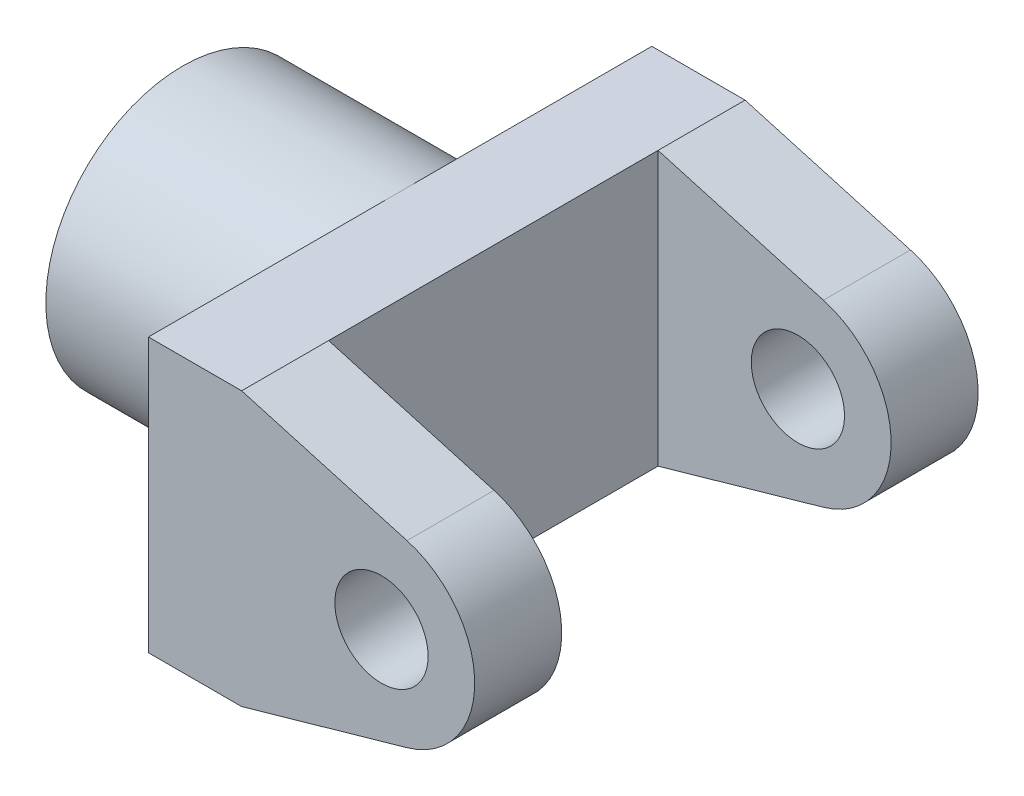
SolidWorks part; units mm, degrees
ref_plane "Front" through (0, 0, 0) normal (0, 0, 1) x (1, 0, 0)
ref_plane "Top" through (0, 0, 0) normal (0, 1, 0) x (1, 0, 0)
ref_plane "Right" through (0, 0, 0) normal (1, 0, 0) x (0, 0, -1)
sketch "Sketch2" plane through (0, 0, 0) normal (0, 0, 1) x (1, 0, 0)
  line L0 (-75, -44) -> (-75, 44)
  line L1 (0, 0) -> (-86.7621, 0) construction
  line L2 (-45, -44) -> (-45, 44)
  line L3 (-75, 44) -> (-45, 44)
  line L4 (-45, 44) -> (8.2128, 28.854)
  line L5 (-75, -44) -> (-45, -44)
  line L6 (-45, -44) -> (8.2128, -28.854)
  circle A0 centre (0, 0) radius 15
  arc A1 (4.5356, -29.6552) -> (4.5356, 29.6552) centre (0, 0) ccw
  circle A2 centre (0, 0) radius 30
  point P6 (-45, 0)
  point P7 (-75, 0)
  point P9 (-75, 0)
  point P15 (-45, 0)
  dimension "D1" = 30
  dimension "D2" = 60
  dimension "D7" = 60
  dimension "D3" = 30
  dimension "D4" = 75
  dimension "D5" = 88
  dimension "D6" = 88
extrude "Boss-Extrude1" add sketch "Sketch2" along normal blind 162
sketch "Sketch3" plane through (0, -44, 0) normal (0, -1, 0) x (1, 0, 0)
  line L0 (-45, 162) -> (-45, 0) construction
  line L1 (-45, 134) -> (30, 134)
  line L2 (-45, 134) -> (-45, 28)
  line L3 (-45, 28) -> (30, 28)
  line L4 (30, 134) -> (30, 28)
  line L5 (30, 0) -> (30, 162) construction
  line L6 (-75, 162) -> (-75, 0) construction
  point P10 (-75, 81)
  point P11 (-45, 81)
  dimension "D1" = 106
extrude "Cut-Extrude1" cut sketch "Sketch3" against normal through all
sketch "Sketch4" plane through (-75, 0, 0) normal (-1, 0, 0) x (0, 0, 1)
  line L0 (0, -44) -> (0, 44) construction
  circle A0 centre (81, 0) radius 44
  circle A1 centre (81, 0) radius 25
  point P3 (37.0051, -0.667)
  dimension "D1" = 88
  dimension "D2" = 50
  dimension "D3" = 81
extrude "Boss-Extrude2" add sketch "Sketch4" along normal blind 70
sketch "Sketch7" plane through (-145, 0, 0) normal (-1, 0, 0) x (0, 0, 1)
  line L1 (56.3221, -4) -> (50.0691, -4)
  line L3 (56.3221, 4) -> (50.0691, 4)
  line L4 (50.0691, -4) -> (50.0691, 4)
  line L5 (56, 0) -> (50.0691, 4) construction
  line L6 (56, 0) -> (50.0691, -4) construction
  circle A0 centre (81, 0) radius 25 construction
  circle A1 centre (81, 0) radius 25
  point P0 (56, 0)
  circle M4 centre (81, 0) radius 25
  dimension "D2" = 8
extrude "Cut-Extrude5" cut sketch "Sketch7" against normal blind 60 contours L4 L1 L3 M4
scale "Scale1" scale about centroid uniform scaling yes scale factor 0.33
